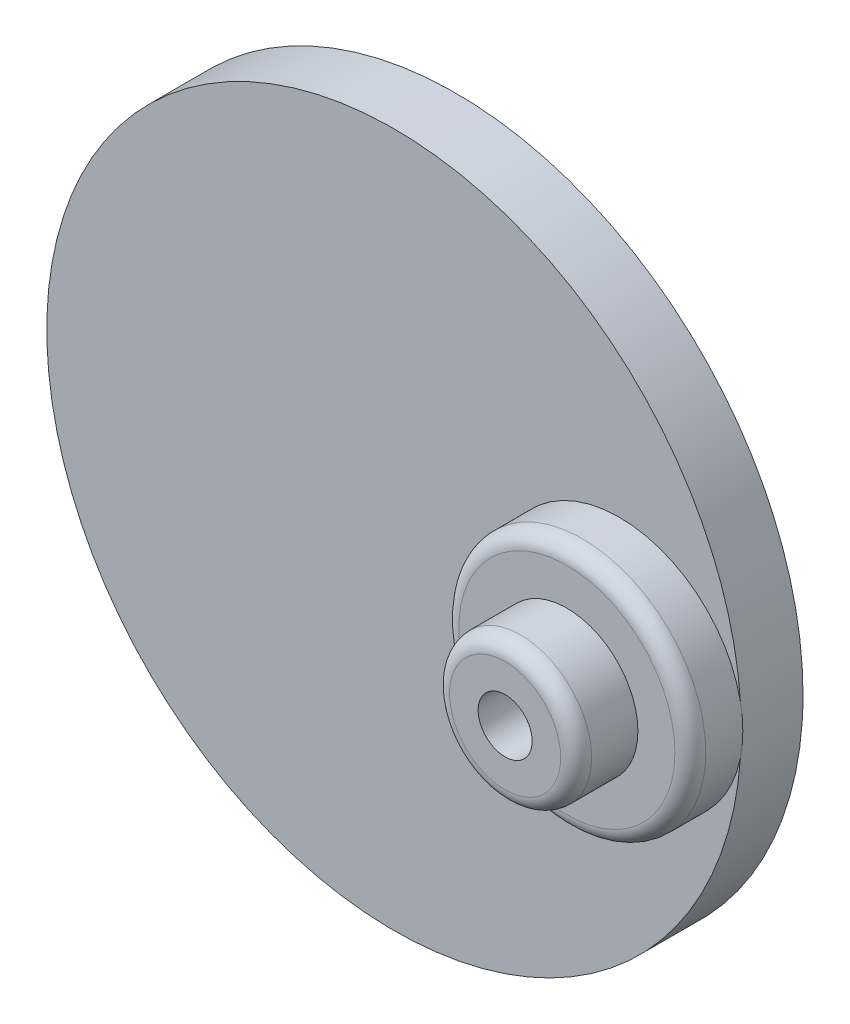
SolidWorks part; units mm, degrees
material "ABS"
ref_plane "Plan de face" through (0, 0, 0) normal (0, 0, 1) x (1, 0, 0)
ref_plane "Plan de dessus" through (0, 0, 0) normal (0, 1, 0) x (1, 0, 0)
ref_plane "Plan de droite" through (0, 0, 0) normal (1, 0, 0) x (0, 0, -1)
sketch "Esquisse1" plane through (0, 0, 0) normal (0, 0, 1) x (1, 0, 0)
  circle A0 centre (0, 0) radius 11.25
  dimension "D1" = 22.5
extrude "Boss.-Extru.1" add sketch "Esquisse1" along normal blind 2
sketch "Esquisse2" plane through (0, 0, 2) normal (0, 0, 1) x (1, 0, 0)
  circle A0 centre (7.3, 0) radius 4
  dimension "D2" = 8
  dimension "D1" = 7.3
extrude "Boss.-Extru.2" add sketch "Esquisse2" along normal blind 1.7
sketch "Esquisse3" plane through (0, 0, 3.7) normal (0, 0, 1) x (1, 0, 0)
  circle A0 centre (7.3, 0) radius 2.3
  dimension "D1" = 4.6
extrude "Boss.-Extru.3" add sketch "Esquisse3" along normal blind 2
fillet "Congé1" radius 0.5 2 edges at (11.3, 0, 3.7) (9.6, 0, 5.7)
sketch "Esquisse4" plane through (0, 0, 0) normal (0, 0, -1) x (-1, 0, 0)
  circle A0 centre (0, 0) radius 3
  dimension "D1" = 6
extrude "Boss.-Extru.4" add sketch "Esquisse4" along normal blind 4
sketch "Esquisse5" plane through (0, 0, -4) normal (0, 0, -1) x (-1, 0, 0)
  circle A0 centre (0, 0) radius 1.45
  dimension "D1" = 2.9
extrude "Enlèv. mat.-Extru.1" cut sketch "Esquisse5" against normal blind 2
hole_wizard "Trou taraudé M2.2x0.451" positions "Esquisse6" profile "Esquisse7" tap size "M2.2x0.45" standard "ISO"
sketch "Esquisse6" plane through (0, 0, 5.7) normal (0, 0, 1) x (1, 0, 0)
  circle A0 centre (7.3, 0) radius 2.3 construction
  point P0 (7.3, 0)
sketch "Esquisse7" plane through (7.3, 0, 5.7) normal (1, 0, 0) x (0, -1, 0)
  line L0 (0, 0) -> (0, 5.5258)
  line L1 (0, 5.5258) -> (0.875, 5)
  line L2 (0.875, 5) -> (0.875, 0)
  line L5 (0.875, 0) -> (0, 0)
  line L10 (0, 5.5258) -> (-0.875, 5) construction
  line L11 (0, -6.35) -> (0, 107.95) construction
  dimension "Diamètre du trou pour taraudage" = 1.75
  dimension "Profondeur du trou pour taraudage" = 5
  dimension "Angle de pointe" = 118
cosmetic thread "Filetage de perçage1" parameters "D1"=4.4, "D2"=2.2
fillet "Congé2" radius 0.2 1 edges at (-3, 0, -4)
